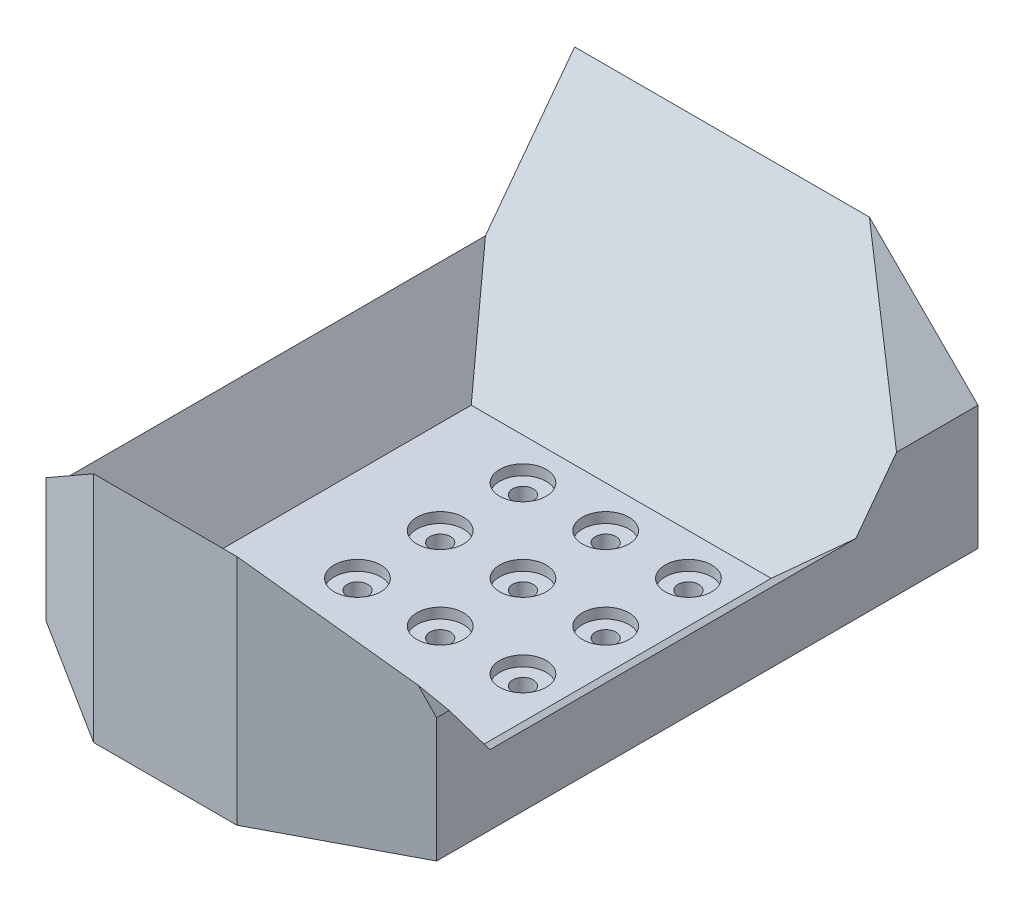
SolidWorks part; units mm, degrees
material "ABS"
ref_plane "前基準面" through (0, 0, 0) normal (0, 0, 1) x (1, 0, 0)
ref_plane "上基準面" through (0, 0, 0) normal (0, 1, 0) x (1, 0, 0)
ref_plane "右基準面" through (0, 0, 0) normal (1, 0, 0) x (0, 0, -1)
sketch "草圖1" plane through (0, 0, 0) normal (0, 1, 0) x (1, 0, 0)
  line L1 (0, 0) -> (62, 0)
  line L2 (0, 0) -> (0, 62)
  line L3 (0, 62) -> (62, 62)
  line L4 (62, 0) -> (62, 62)
  dimension "D1" = 62
  dimension "D2" = 62
extrude "填料-伸長1" add sketch "草圖1" along normal blind 19
sketch "草圖4" plane through (0, 19, 0) normal (0, 1, 0) x (1, 0, 0)
  line L5 (2, 60) -> (60, 60)
  line L6 (2, 60) -> (2, 2)
  line L7 (2, 2) -> (60, 2)
  line L8 (60, 60) -> (60, 2)
  dimension "D3" = 58
  dimension "D4" = 58
extrude "除料-伸長1" cut sketch "草圖4" against normal blind 17
sketch "草圖5" plane through (0, 19, 0) normal (0, 1, 0) x (1, 0, 0)
  line L1 (0, 0) -> (-8, 0)
  line L2 (0, 0) -> (0, 62)
  line L3 (0, 62) -> (-8, 62)
  line L4 (-8, 0) -> (-8, 62)
  dimension "D1" = 8
extrude "填料-伸長2" add sketch "草圖5" against normal blind 19
sketch "草圖7" plane through (0, 0, -60) normal (0, 0, 1) x (1, 0, 0)
  line L1 (60, 2) -> (2, 2)
  line L2 (60, 2) -> (60, 19)
  line L3 (60, 19) -> (2, 19)
  line L4 (2, 2) -> (2, 19)
extrude "除料-伸長2" cut sketch "草圖7" against normal blind 19
sketch "草圖8" plane through (0, 0, -62) normal (0, 0, -1) x (-1, 0, 0)
  line L0 (-2, 2) -> (8, 19)
  line L1 (8, 19) -> (-2, 19)
  line L2 (-2, 19) -> (-2, 2)
extrude "除料-伸長3" cut sketch "草圖8" against normal blind 108
sketch "草圖9" plane through (0, 0, -62) normal (0, 0, -1) x (-1, 0, 0)
  line L0 (8, 0) -> (8, 19) construction
  line L1 (-62, 0) -> (8, 0)
  line L2 (-62, 0) -> (-62, 2)
  line L3 (-62, 2) -> (8, 2)
  line L4 (8, 0) -> (8, 2)
extrude "填料-伸長3" add sketch "草圖9" along normal blind 28
sketch "草圖10" plane through (0, 2, 0) normal (0, 1, 0) x (1, 0, 0)
  line L1 (62, 90) -> (-8, 90)
  line L2 (62, 90) -> (62, 62)
  line L3 (62, 62) -> (-8, 62)
  line L4 (-8, 90) -> (-8, 62)
extrude "填料-伸長4" add sketch "草圖10" along normal blind 40
sketch "草圖11" plane through (-8, 0, 0) normal (-1, 0, 0) x (0, 0, 1)
  line L0 (-90, 42) -> (-62, 2)
  line L1 (-90, 42) -> (-62, 42)
  line L2 (-90, 0) -> (0, 0) construction
  line L3 (-62, 0) -> (-62, 2)
  line L4 (-62, 42) -> (-62, 2)
  dimension "D1" = 2
extrude "除料-伸長5" cut sketch "草圖11" against normal blind 90 contours L4 L0 L1
sketch "草圖14" plane through (0, 19, 0) normal (0, 1, 0) x (1, 0, 0)
  line L1 (2, 0) -> (62, 0)
  line L2 (2, 0) -> (2, 62)
  line L3 (2, 62) -> (62, 62)
  line L4 (62, 0) -> (62, 62)
extrude "除料-伸長6" cut sketch "草圖14" against normal blind 17
sketch "草圖15" plane through (62, 0, 0) normal (1, 0, 0) x (0, 0, -1)
  line L1 (62, 2) -> (0, 2)
  line L2 (62, 2) -> (62, 0)
  line L3 (62, 0) -> (0, 0)
  line L4 (0, 2) -> (0, 0)
extrude "填料-伸長6" add sketch "草圖15" along normal blind 8
sketch "草圖18" plane through (0, 2, 0) normal (0, 1, 0) x (1, 0, 0)
  line L0 (2, 0) -> (70, 0) construction
  line L1 (70, 62) -> (60, 62)
  line L2 (70, 62) -> (70, 0)
  line L3 (70, 0) -> (60, 0)
  line L4 (60, 62) -> (60, 0)
  dimension "D1" = 10
extrude "填料-伸長8" add sketch "草圖18" along normal blind 19
sketch "草圖19" plane through (0, 0, 0) normal (0, 0, 1) x (1, 0, 0)
  line L0 (60, 2) -> (70, 10.5)
  line L1 (70, 21) -> (70, 0) construction
  line L2 (70, 10.5) -> (70, 21)
  line L3 (70, 21) -> (60, 21)
  line L4 (60, 21) -> (60, 2)
extrude "除料-伸長7" cut sketch "草圖19" against normal blind 62
sketch "草圖20" plane through (62, 0, 0) normal (1, 0, 0) x (0, 0, -1)
  line L0 (90, 42) -> (62, 2)
  line L1 (62, 2) -> (62, 0)
  line L2 (62, 0) -> (90, 0)
  line L3 (90, 0) -> (90, 42)
extrude "填料-伸長9" add sketch "草圖20" along normal blind 8
sketch "草圖23" plane through (0, 0, 0) normal (0, 0, 1) x (1, 0, 0)
  line L0 (70, 10.5) -> (70, 0) construction
  line L1 (-8, 0) -> (70, 0)
  line L2 (-8, 0) -> (-8, 2)
  line L3 (-8, 2) -> (70, 2)
  line L4 (70, 0) -> (70, 2)
  dimension "D1" = 2
extrude "填料-伸長13" add sketch "草圖23" along normal blind 28
sketch "草圖25" plane through (0, 2, 0) normal (0, 1, 0) x (1, 0, 0)
  line L1 (70, 0) -> (-8, 0)
  line L2 (70, 0) -> (70, -28)
  line L3 (70, -28) -> (-8, -28)
  line L4 (-8, 0) -> (-8, -28)
extrude "填料-伸長14" add sketch "草圖25" along normal blind 40
sketch "草圖26" plane through (-8, 0, 0) normal (-1, 0, 0) x (0, 0, 1)
  line L0 (0, 0) -> (0, 2)
  line L4 (28, 42) -> (0, 42)
  line L5 (0, 42) -> (0, 2)
  line L6 (28, 42) -> (0, 2)
  dimension "D1" = 2
  dimension "D2" = 28
extrude "除料-伸長8" cut sketch "草圖26" against normal blind 99
sketch "草圖34" plane through (70, 0, 0) normal (1, 0, 0) x (0, 0, -1)
  line L0 (0, 2) -> (2, 2)
  line L1 (2, 2) -> (-28, 42)
  line L2 (-28, 42) -> (-28, 2)
  line L3 (-28, 0) -> (-28, 42) construction
  line L4 (-28, 2) -> (2, 2)
  line M2 (0, 2) -> (-28, 42)
  line M3 (-28, 42) -> (-28, 0)
  line M8 (0, 10.5) -> (0, 2)
  dimension "D1" = 2
extrude "填料-伸長19" add sketch "草圖34" against normal blind 78 contours L4 M3 M2 | L1 M8 M2 | L0 L1 M8
sketch "草圖36" plane through (-8, 0, 0) normal (-1, 0, 0) x (0, 0, 1)
  line L0 (-62, 2) -> (-60, 2)
  line L1 (-90, 42) -> (-60, 2)
  line L2 (-60, 2) -> (-90, 2)
  line L3 (-90, 0) -> (-90, 42) construction
  line L4 (-90, 2) -> (-90, 42)
  line M5 (-62, 19) -> (-62, 2)
  line M6 (-62, 2) -> (-90, 42)
  line M7 (-90, 42) -> (-90, 0)
  dimension "D1" = 2
extrude "填料-伸長20" add sketch "草圖36" against normal blind 78 contours L2 M6 M7 | L1 M6 M5 | L1 L0 M5
sketch "草圖37" plane through (0, 0, -62) normal (0, 0, -1) x (-1, 0, 0)
  line L0 (8, 4.6667) -> (-0.4314, 4.6667)
  line L1 (-0.4314, 4.6667) -> (8, 19)
  line L2 (8, 19) -> (8, 4.6667)
extrude "填料-伸長21" add sketch "草圖37" along normal blind 24
sketch "草圖38" plane through (0, 0, -62) normal (0, 0, -1) x (-1, 0, 0)
  line L0 (-63.1373, 4.6667) -> (-70, 4.6667)
  line L1 (-70, 4.6667) -> (-70, 10.5)
  line L2 (-70, 10.5) -> (-63.1373, 4.6667)
extrude "填料-伸長22" add sketch "草圖38" along normal blind 24
sketch "草圖39" plane through (0, 0, 0) normal (0, 0, 1) x (1, 0, 0)
  line L0 (-8, 19) -> (-8, 4.6667)
  line L1 (-8, 4.6667) -> (0.4314, 4.6667)
  line L2 (0.4314, 4.6667) -> (-8, 19)
extrude "填料-伸長23" add sketch "草圖39" along normal blind 24
sketch "草圖40" plane through (0, 0, 0) normal (0, 0, 1) x (1, 0, 0)
  line L0 (70, 10.5) -> (63.1373, 4.6667)
  line L1 (63.1373, 4.6667) -> (70, 4.6667)
  line L2 (70, 4.6667) -> (70, 10.5)
extrude "填料-伸長24" add sketch "草圖40" along normal blind 24
sketch "草圖43" plane through (0, 0, 0) normal (0, -1, 0) x (-1, 0, 0)
  line L1 (8, -28) -> (-70, -28)
  line L2 (8, -28) -> (8, 90)
  line L3 (8, 90) -> (-70, 90)
  line L4 (-70, -28) -> (-70, 90)
extrude "填料-伸長25" add sketch "草圖43" along normal blind 1
sketch "草圖46" plane through (0, 0, -90) normal (0, 0, -1) x (-1, 0, 0)
  line L0 (-70, 42) -> (-60, 42)
  line L1 (-70, 42) -> (8, 42) construction
  line L2 (-70, 42) -> (-70, 21)
  line L3 (-70, -1) -> (-70, 42) construction
  line L4 (-70, 21) -> (-60, 42)
  dimension "D1" = 10
  dimension "D2" = 21
extrude "除料-伸長14" cut sketch "草圖46" against normal blind 127
sketch "草圖47" plane through (0, 0, 28) normal (0, 0, 1) x (1, 0, 0)
  line L0 (-8, 42) -> (2, 42)
  line L1 (-8, 42) -> (60, 42) construction
  line L2 (-8, 42) -> (-8, 21)
  line L3 (-8, 42) -> (-8, -1) construction
  line L4 (-8, 21) -> (2, 42)
  dimension "D1" = 10
  dimension "D2" = 21
extrude "除料-伸長15" cut sketch "草圖47" against normal blind 80
sketch "草圖49" plane through (0, 2, 0) normal (0, 1, 0) x (1, 0, 0)
  circle A0 centre (52, 52) radius 2
  circle A1 centre (36, 52) radius 2
  circle A2 centre (20, 52) radius 2
  circle A3 centre (36, 36) radius 2
  circle A4 centre (20, 36) radius 2
  circle A5 centre (36, 20) radius 2
  circle A6 centre (20, 20) radius 2
  circle A7 centre (52, 36) radius 2
  circle A8 centre (52, 20) radius 2
  dimension "D3" = 4
  dimension "D1" = 3
  dimension "D2" = 3
extrude "除料-伸長17" cut sketch "草圖49" against normal blind 19
sketch "草圖50" plane through (0, 2, 0) normal (0, 1, 0) x (1, 0, 0)
  circle A0 centre (52, 20) radius 4.5
  circle A1 centre (36, 20) radius 4.5
  circle A2 centre (20, 20) radius 4.5
  circle A3 centre (36, 36) radius 4.5
  circle A4 centre (20, 36) radius 4.5
  circle A5 centre (36, 52) radius 4.5
  circle A6 centre (20, 52) radius 4.5
  circle A7 centre (52, 36) radius 4.5
  circle A8 centre (52, 52) radius 4.5
  dimension "D1" = 9
  dimension "D2" = 3
  dimension "D3" = 3
extrude "除料-伸長18" cut sketch "草圖50" against normal blind 2
sketch "草圖55" plane through (0, 0, -90) normal (0, 0, -1) x (-1, 0, 0)
  circle A1 centre (-5, 7) radius 2
  circle A2 centre (-13, 7) radius 2
  circle A3 centre (-5, 15) radius 2
  circle A4 centre (-13, 15) radius 2
  circle A5 centre (-5, 23) radius 2
  circle A6 centre (-13, 23) radius 2
  circle A7 centre (3, 15) radius 2
  circle A8 centre (3, 23) radius 2
extrude "除料-伸長20" cut sketch "草圖55" against normal blind 7.5
sketch "草圖57" plane through (0, 0, -90) normal (0, 0, -1) x (-1, 0, 0)
  line L2 (8, -1) -> (-70, -1) construction
  line L3 (-28.0955, 31.1638) -> (8, 31.1638)
  line L4 (-28.0955, 31.1638) -> (-28.0955, -1)
  line L5 (-28.0955, -1) -> (8, -1)
  line L6 (8, 31.1638) -> (8, -1)
extrude "填料-伸長26" add sketch "草圖57" against normal blind 7
sketch "草圖63" plane through (0, 0, -90) normal (0, 0, -1) x (-1, 0, 0)
  circle A0 centre (-64, 7) radius 1.8
  circle A1 centre (-56, 7) radius 1.8
  circle A2 centre (-48, 7) radius 1.8
  circle A3 centre (-56, 15) radius 1.8
  circle A4 centre (-48, 15) radius 1.8
  circle A5 centre (-56, 23) radius 1.8
  circle A6 centre (-48, 23) radius 1.8
  circle A7 centre (-64, 15) radius 1.8
  circle A8 centre (-64, 23) radius 1.8
  dimension "D3" = 3.6
  dimension "D4" = 3
  dimension "D5" = 3
extrude "除料-伸長23" cut sketch "草圖63" against normal blind 7.5
sketch "草圖64" plane through (0, -1, 0) normal (0, -1, 0) x (-1, 0, 0)
  line L0 (-70, 90) -> (-70, -28) construction
  line L1 (8, -28) -> (-70, -28)
  line L2 (8, -28) -> (8, 90)
  line L3 (8, 90) -> (-70, 90)
  line L4 (-70, -28) -> (-70, 90)
  line L5 (8, 90) -> (-70, 90) construction
extrude "填料-伸長27" add sketch "草圖64" along normal blind 1
sketch "草圖65" plane through (0, -1, 0) normal (0, 1, 0) x (1, 0, 0)
  circle A0 centre (52, 52) radius 2
  circle A1 centre (36, 52) radius 2
  circle A2 centre (20, 52) radius 2
  circle A3 centre (36, 36) radius 2
  circle A4 centre (20, 36) radius 2
  circle A5 centre (36, 20) radius 2
  circle A6 centre (20, 20) radius 2
  circle A7 centre (52, 36) radius 2
  circle A8 centre (52, 20) radius 2
  dimension "D1" = 3
  dimension "D2" = 3
extrude "除料-伸長24" cut sketch "草圖65" against normal blind 29
sketch "草圖66" plane through (0, -2, 0) normal (0, -1, 0) x (-1, 0, 0)
  line L1 (8, 90) -> (-70, 90)
  line L2 (8, 90) -> (8, -28)
  line L3 (8, -28) -> (-70, -28)
  line L4 (-70, 90) -> (-70, -28)
extrude "填料-伸長28" add sketch "草圖66" along normal blind 1
sketch "草圖68" plane through (0, -2, 0) normal (0, 1, 0) x (1, 0, 0)
  circle A0 centre (20, 20) radius 2
  circle A1 centre (36, 20) radius 2
  circle A2 centre (52, 20) radius 2
  circle A3 centre (36, 36) radius 2
  circle A4 centre (52, 36) radius 2
  circle A5 centre (36, 52) radius 2
  circle A6 centre (52, 52) radius 2
  circle A7 centre (20, 36) radius 2
  circle A8 centre (20, 52) radius 2
  dimension "D1" = 3
  dimension "D2" = 3
extrude "除料-伸長25" cut sketch "草圖68" against normal blind 28
sketch "草圖69" plane through (0, -3, 0) normal (0, -1, 0) x (1, 0, 0)
  line L0 (44.6884, 28) -> (70, 14.696)
  line L1 (70, 28) -> (-8, 28) construction
  line L2 (70, -90) -> (70, 28) construction
  line L3 (70, 14.696) -> (70, 28)
  line L4 (70, 28) -> (44.6884, 28)
  line L5 (153.3698, -29.1241) -> (224.8578, -66.6989) construction
  line L6 (-8, 12.2288) -> (-8, 28)
  line L7 (-8, 28) -> (-8, -90) construction
  line L8 (-8, 28) -> (16.9735, 28)
  line L9 (16.9735, 28) -> (-8, 12.2288)
  line L10 (-54.9365, -17.4124) -> (5.9404, 21.0324) construction
extrude "除料-伸長26" cut sketch "草圖69" against normal through all
sketch "草圖70" plane through (0, -3, 0) normal (0, -1, 0) x (1, 0, 0)
  line L0 (44.8465, -75.0346) -> (38.0824, -79.3063) construction
  line L1 (46.9823, -78.4167) -> (40.2182, -82.6883)
  line L2 (42.7107, -71.6526) -> (35.9466, -75.9242)
  circle A0 centre (44.8465, -75.0346) radius 4
  circle A1 centre (38.0824, -79.3063) radius 4
  circle A2 centre (21.8486, -89.5582) radius 4
  arc A3 (46.9823, -78.4167) -> (42.7107, -71.6526) centre (44.8465, -75.0346) ccw
  arc A4 (35.9466, -75.9242) -> (40.2182, -82.6883) centre (38.0824, -79.3063) ccw
  point P9 (41.4645, -77.1705)
  dimension "D1" = 8
  dimension "D2" = 8
  dimension "D3" = 8
  dimension "D4" = 8
  dimension "D5" = 4
extrude "除料-伸長27" cut sketch "草圖70" against normal blind 5.5
sketch "草圖71" plane through (0, 0, -90) normal (0, 0, -1) x (-1, 0, 0)
  line L0 (-70, 21) -> (-60, 42)
  line L1 (-60, 42) -> (-49, 42)
  line L2 (-60, 42) -> (8, 42) construction
  line L3 (-49, 42) -> (-70, 21)
  dimension "D1" = 45
extrude "除料-伸長28" cut sketch "草圖71" against normal up to next
